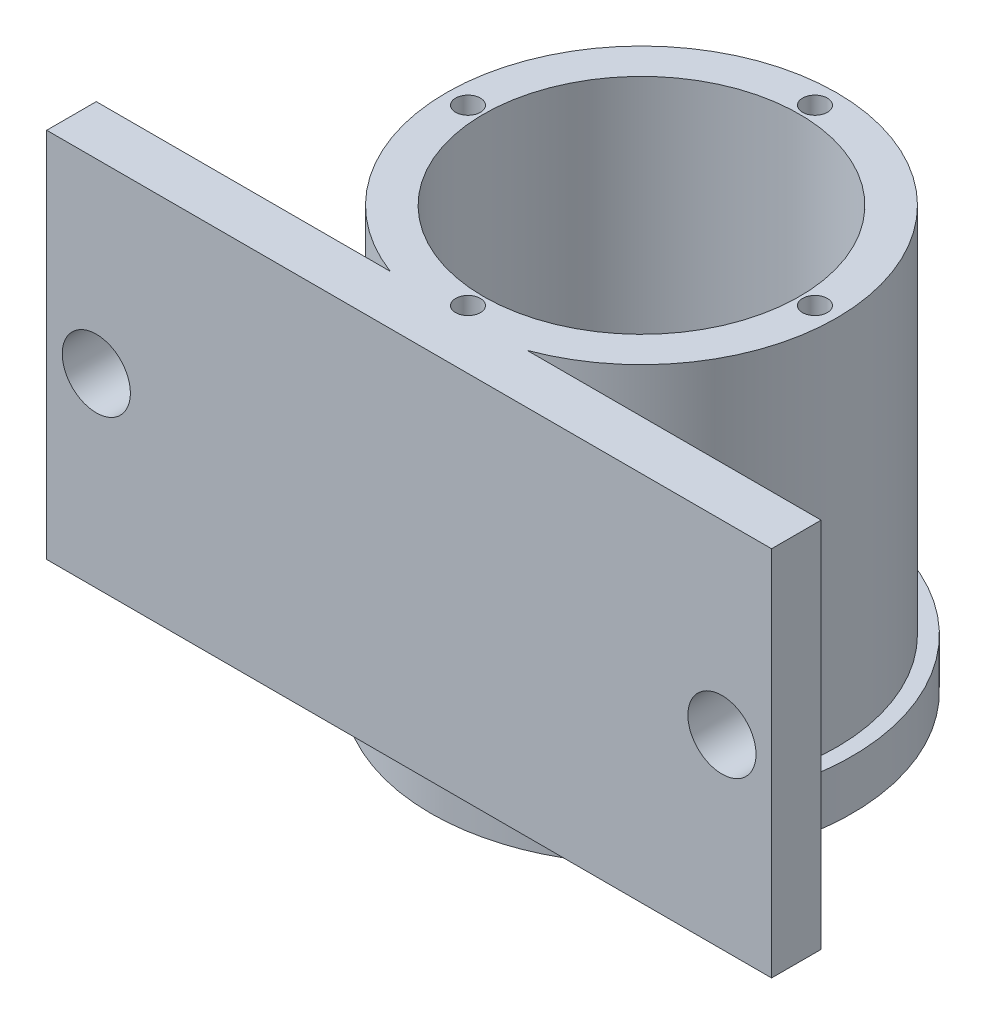
SolidWorks part; units mm, degrees
ref_plane "Front Plane" through (0, 0, 0) normal (0, 0, 1) x (1, 0, 0)
ref_plane "Top Plane" through (0, 0, 0) normal (0, 1, 0) x (1, 0, 0)
ref_plane "Right Plane" through (0, 0, 0) normal (1, 0, 0) x (0, 0, -1)
sketch "Sketch1" plane through (0, 0, 0) normal (0, 1, 0) x (1, 0, 0)
  circle A0 centre (0, 0) radius 17
  dimension "D1" = 34
extrude "Boss-Extrude2" add sketch "Sketch1" along normal blind 4 contours A0
shell "Shell1" thickness 2
sketch "Sketch2" plane through (0, 4, 0) normal (0, 1, 0) x (1, 0, 0)
  circle A0 centre (0, 0) radius 14.25
  dimension "D1" = 28.5
sketch "Sketch14" plane through (0, 4, 0) normal (0, 1, 0) x (1, 0, 0)
  circle A1 centre (0, 0) radius 15.75
  dimension "D1" = 31.5
extrude "Boss-Extrude7" add sketch "Sketch14" along normal blind 30
shell "Shell4" thickness 3
ref_plane "Plane2" through (0, 0, 15.75) normal (0, 0, 1) x (1, 0, 0)
sketch "Sketch16" plane through (0, 0, 15.75) normal (0, 0, 1) x (1, 0, 0)
  line L0 (0, 4) -> (0, 34) construction
  line L1 (17, 4) -> (-17, 4) construction
  line L2 (15.75, 34) -> (-15.75, 34) construction
  line L3 (-15.75, 19) -> (15.75, 19) construction
  line L4 (-15.75, 34) -> (-15.75, 4) construction
  line L5 (15.75, 4) -> (15.75, 34) construction
  line L7 (-29.2495, 34) -> (29.2495, 34)
  line L8 (-29.2495, 34) -> (-29.2495, 4)
  line L9 (-29.2495, 4) -> (29.2495, 4)
  line L10 (29.2495, 34) -> (29.2495, 4)
  line L11 (-29.2495, 34) -> (29.2495, 4) construction
  line L12 (-29.2495, 4) -> (29.2495, 34) construction
  point P12 (0, 19)
extrude "Boss-Extrude12" add sketch "Sketch16" along normal blind 3 and the other way blind 1
sketch "Sketch17" plane through (0, 0, 18.75) normal (0, 0, 1) x (1, 0, 0)
  line L0 (0, 34) -> (0, 4) construction
  line L1 (29.2495, 34) -> (-29.2495, 34) construction
  line L2 (-8.4521, 4) -> (8.4521, 4) construction
  line L3 (-29.2495, 19) -> (29.2495, 19) construction
  line L4 (-29.2495, 34) -> (-29.2495, 4) construction
  line L5 (29.2495, 4) -> (29.2495, 34) construction
  circle A0 centre (-25.2447, 19) radius 2.75
  circle A1 centre (25.2447, 19) radius 2.75
  dimension "D1" = 5.5
extrude "Cut-Extrude4" cut sketch "Sketch17" against normal blind 5
sketch "Sketch18" plane through (0, 34, 0) normal (0, 1, 0) x (1, 0, 0)
  circle A0 centre (0, 14) radius 1
  circle A1 centre (14, 0) radius 1
  circle A2 centre (0, -14) radius 1
  circle A3 centre (-14, 0) radius 1
  point P12 (0, 0)
  dimension "D1" = 2
  dimension "D2" = 14
  dimension "D3" = 4
extrude "Cut-Extrude5" cut sketch "Sketch18" against normal blind 7
